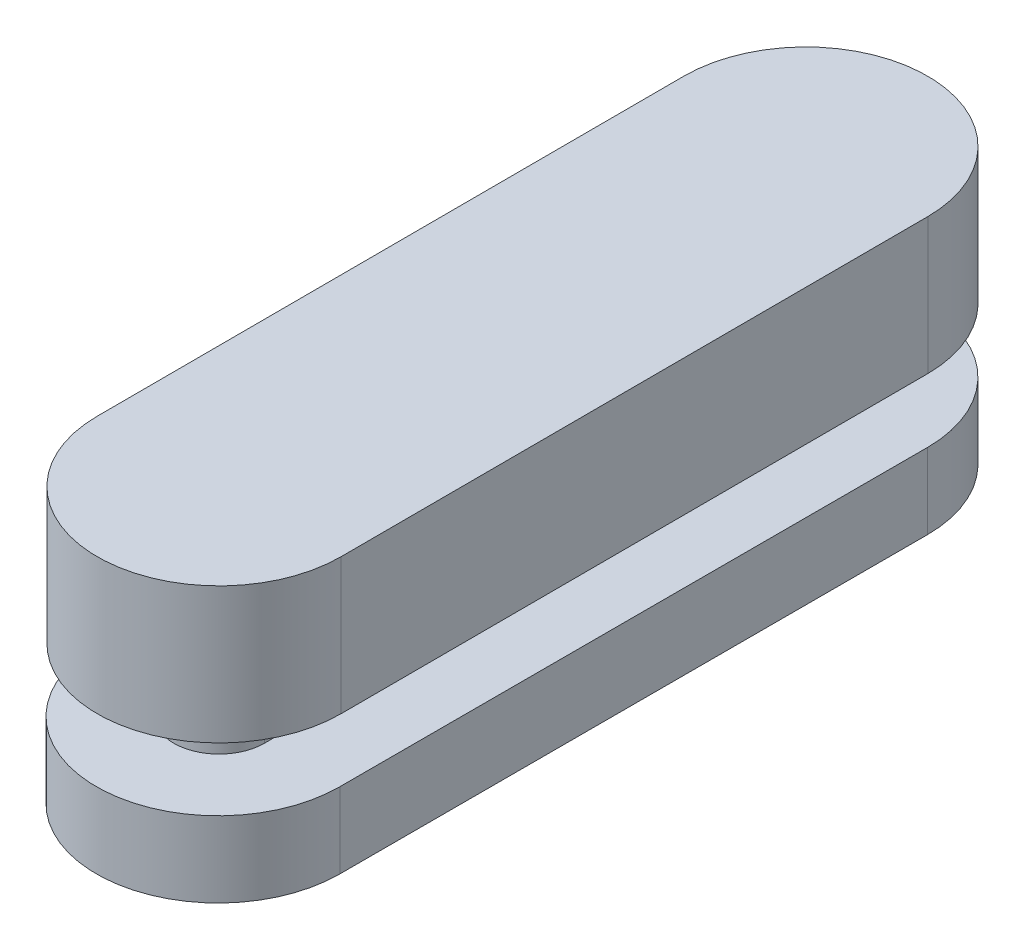
SolidWorks part; units mm, degrees
ref_plane "Front" through (0, 0, 0) normal (0, 0, 1) x (1, 0, 0)
ref_plane "Top" through (0, 0, 0) normal (0, 1, 0) x (1, 0, 0)
ref_plane "Right" through (0, 0, 0) normal (1, 0, 0) x (0, 0, -1)
sketch "Sketch1" plane through (0, 0, 0) normal (0, 1, 0) x (1, 0, 0)
  line L0 (0, 0) -> (0, -35) construction
  line L1 (7.25, 0) -> (7.25, -35)
  line L2 (-7.25, 0) -> (-7.25, -35)
  arc A0 (7.25, 0) -> (-7.25, 0) centre (0, 0) ccw
  arc A1 (-7.25, -35) -> (7.25, -35) centre (0, -35) ccw
  point P3 (0, -17.5)
extrude "Boss-Extrude1" add sketch "Sketch1" along normal blind 4.5
sketch "Sketch3" plane through (0, 4.5, 0) normal (0, 1, 0) x (1, 0, 0)
  line L1 (-2.6226, -0.0113) -> (2.7638, -0.0113)
  line L2 (-2.6226, -0.0113) -> (-2.6226, -35.0113)
  line L3 (-2.6226, -35.0113) -> (2.7638, -35.0113)
  line L4 (2.7638, -0.0113) -> (2.7638, -35.0113)
  circle A0 centre (0.0706, -0.0113) radius 2.7299
  circle A1 centre (0.0706, -35.0113) radius 2.6932
  dimension "D1" = 35
extrude "Boss-Extrude2" add sketch "Sketch3" along normal blind 3.8 contours L4 A0 L2 L1 | A1 L4 A0 L2 | L3 A1 | L3 A1 | L2 A0 L4 L1
sketch "Sketch4" plane through (0, 8.3, 0) normal (0, 1, 0) x (1, 0, 0)
  line L0 (0, 0) -> (0.0706, -35.0113) construction
  line L1 (7.2531, 0.0146) -> (7.3237, -34.9967)
  line L2 (-7.2531, -0.0146) -> (-7.1825, -35.0259)
  arc A0 (7.2531, 0.0146) -> (-7.2531, -0.0146) centre (0, 0) ccw
  arc A1 (-7.1825, -35.0259) -> (7.3237, -34.9967) centre (0.0706, -35.0113) ccw
  point P4 (0.0353, -17.5056)
extrude "Boss-Extrude3" add sketch "Sketch4" along normal blind 8.1
